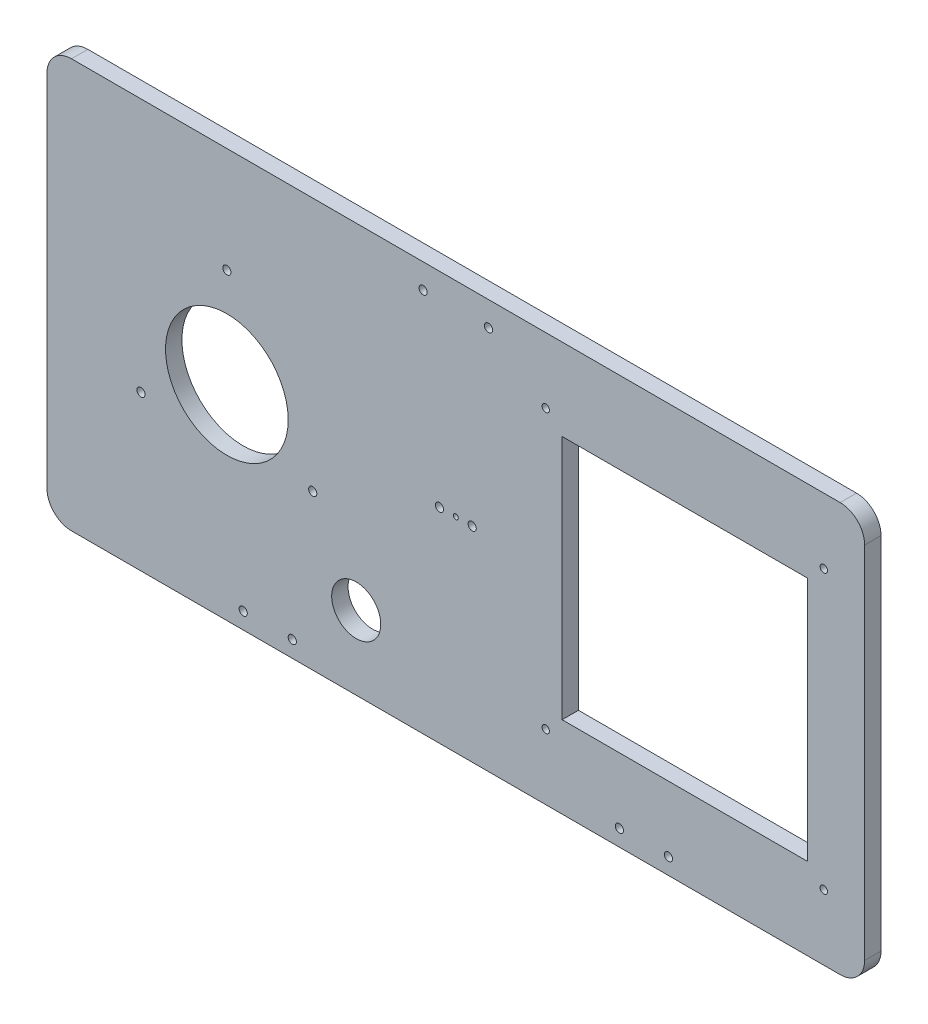
SolidWorks part; units mm, degrees
ref_plane "Alzado" through (0, 0, 0) normal (0, 0, 1) x (1, 0, 0)
ref_plane "Planta" through (0, 0, 0) normal (0, 1, 0) x (1, 0, 0)
ref_plane "Vista lateral" through (0, 0, 0) normal (1, 0, 0) x (0, 0, -1)
sketch "Croquis1" plane through (0, 0, 0) normal (0, 0, 1) x (1, 0, 0)
  line L0 (465, 125) -> (500, 125) construction
  line L1 (15, 0) -> (485, 0)
  line L2 (0, 15) -> (0, 235)
  line L3 (15, 250) -> (485, 250)
  line L4 (500, 15) -> (500, 235)
  line L5 (315, 50) -> (465, 50)
  line L6 (315, 50) -> (315, 200)
  line L7 (315, 200) -> (465, 200)
  line L8 (465, 50) -> (465, 200)
  line L9 (110, 250) -> (110, 0) construction
  line L10 (110, 125) -> (162.5, 94.6891) construction
  line L11 (162.5, 94.6891) -> (110, 185.6218) construction
  line L12 (110, 185.6218) -> (57.5, 94.6891) construction
  line L13 (57.5, 94.6891) -> (162.5, 94.6891) construction
  line L14 (83.75, 140.1554) -> (110, 125) construction
  line L15 (57.5, 94.6891) -> (136.25, 140.1554) construction
  line L16 (250, 250) -> (250, 0) construction
  line L17 (0, 125) -> (500, 125) construction
  line L18 (230, 235) -> (270, 235) construction
  line L23 (240, 125) -> (260, 125) construction
  line L25 (305, 40) -> (305, 210) construction
  line L26 (305, 210) -> (475, 210) construction
  line L27 (475, 40) -> (475, 210) construction
  line L28 (305, 40) -> (475, 40) construction
  line L29 (310, 45) -> (310, 205) construction
  line L30 (310, 205) -> (470, 205) construction
  line L31 (470, 45) -> (470, 205) construction
  line L32 (310, 45) -> (470, 45) construction
  line L33 (390, 200) -> (390, 50) construction
  line L66 (340, 10) -> (350, 10) construction
  line L67 (340, 0) -> (390, 0) construction
  line L68 (340, 0) -> (340, 20) construction
  line L69 (340, 20) -> (390, 20) construction
  line L70 (390, 0) -> (390, 20) construction
  line L71 (380, 10) -> (390, 10) construction
  line L72 (350, 10) -> (380, 10) construction
  line L73 (365, 10) -> (365, 20) construction
  circle A0 centre (110, 125) radius 97.5 construction
  circle A1 centre (110, 185.6218) radius 2.5
  circle A2 centre (162.5, 94.6891) radius 2.5
  circle A3 centre (57.5, 94.6891) radius 2.5
  circle A4 centre (110, 125) radius 37.5
  arc A5 (485, 250) -> (500, 235) centre (485, 235) cw
  arc A6 (485, 0) -> (500, 15) centre (485, 15) ccw
  arc A7 (15, 0) -> (0, 15) centre (15, 15) cw
  arc A8 (0, 235) -> (15, 250) centre (15, 235) cw
  circle A13 centre (230, 235) radius 2.5
  circle A14 centre (270, 235) radius 2.5
  circle A15 centre (189.0965, 45) radius 15
  circle A16 centre (475, 210) radius 2.25
  circle A17 centre (305, 210) radius 2.25
  circle A18 centre (305, 40) radius 2.25
  circle A19 centre (475, 40) radius 2.25
  circle A20 centre (350, 10) radius 2.5
  circle A21 centre (380, 10) radius 2.5
  circle A24 centre (120, 10) radius 2.5
  circle A25 centre (150, 10) radius 2.5
  circle A26 centre (240, 125) radius 2.5
  circle A27 centre (260, 125) radius 2.5
  circle A28 centre (250, 125) radius 1.5
  point P29 (500, 0)
  point P32 (0, 0)
  point P35 (0, 250)
  point P46 (250, 125)
  point P53 (250, 235)
  point P78 (250, 125)
  dimension "D5" = 195
  dimension "D8" = 5
  dimension "D9" = 75
  dimension "D10" = 15
  dimension "D11" = 30
  dimension "D18" = 5
  dimension "D20" = 30
  dimension "D13" = 5
  dimension "D17" = 4.5
  dimension "D24" = 3
  dimension "D1" = 500
  dimension "D2" = 250
  dimension "D3" = 150
  dimension "D4" = 35
  dimension "D6" = 110
  dimension "D7" = 105
  dimension "D12" = 50
  dimension "D14" = 45
  dimension "D15" = 90
  dimension "D16" = 20
  dimension "D19" = 40
  dimension "D21" = 10
  dimension "D23" = 20
  dimension "D27" = 15
  dimension "D22" = 5
extrude "Saliente-Extruir1" add sketch "Croquis1" along normal blind 10
